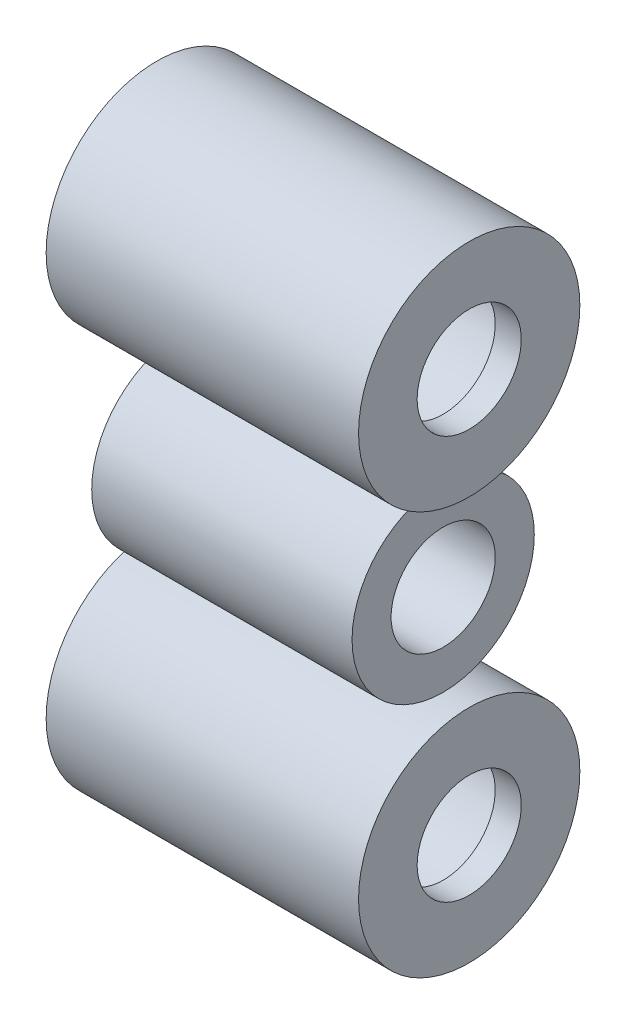
SolidWorks part; units mm, degrees
ref_plane "Front Plane" through (0, 0, 0) normal (0, 0, 1) x (1, 0, 0)
ref_plane "Top Plane" through (0, 0, 0) normal (0, 1, 0) x (1, 0, 0)
ref_plane "Right Plane" through (0, 0, 0) normal (1, 0, 0) x (0, 0, -1)
sketch "Sketch1" plane through (0, 0, 0) normal (1, 0, 0) x (0, 0, -1)
  circle A0 centre (0, 0) radius 7
  circle A1 centre (0, 0) radius 4
  dimension "D1" = 14
  dimension "D2" = 8
extrude "Boss-Extrude1" add sketch "Sketch1" along normal mid plane 20
sketch "Sketch2" plane through (0, 0, 0) normal (0, 0, 1) x (1, 0, 0)
  line L0 (-16.9103, 15.5) -> (14.6495, 15.5) construction
  line L1 (-12, 24) -> (12, 24)
  line L2 (12, 24) -> (12, 19.5)
  line L3 (12, 19.5) -> (10, 19.5)
  line L4 (10, 19.5) -> (10, 22)
  line L5 (10, 22) -> (-10, 22)
  line L6 (-10, 22) -> (-10, 19.5)
  line L7 (-10, 19.5) -> (-12, 19.5)
  line L8 (-12, 19.5) -> (-12, 24)
  line L9 (0, 33.5272) -> (0, 0) construction
  dimension "D1" = 15.5
  dimension "D2" = 20
  dimension "D3" = 2
  dimension "D4" = 4
  dimension "D5" = 6.5
  dimension "D6" = 2
revolve "Revolve1" add sketch "Sketch2" angle 360 about L0
sketch "Sketch3" plane through (0, 0, 0) normal (0, 0, 1) x (1, 0, 0)
  line L0 (-16.9103, -15.5) -> (14.6495, -15.5) construction
  line L1 (-12, -24) -> (12, -24)
  line L2 (12, -24) -> (12, -19.5)
  line L3 (12, -19.5) -> (10, -19.5)
  line L4 (10, -19.5) -> (10, -22)
  line L5 (10, -22) -> (-10, -22)
  line L6 (-10, -22) -> (-10, -19.5)
  line L7 (-10, -19.5) -> (-12, -19.5)
  line L8 (-12, -19.5) -> (-12, -24)
  line L9 (0, -28.8767) -> (0, 0) construction
  dimension "D1" = 15.5
  dimension "D2" = 20
  dimension "D3" = 2
  dimension "D4" = 4
  dimension "D5" = 6.5
  dimension "D6" = 2
revolve "Revolve2" add sketch "Sketch3" angle 360 about L0
